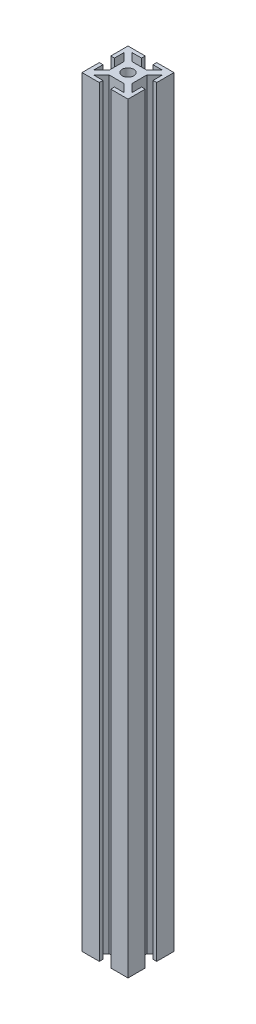
SolidWorks part; units mm, degrees
ref_plane "Front Plane" through (0, 0, 0) normal (0, 0, 1) x (1, 0, 0)
ref_plane "Top Plane" through (0, 0, 0) normal (0, 1, 0) x (1, 0, 0)
ref_plane "Right Plane" through (0, 0, 0) normal (1, 0, 0) x (0, 0, -1)
sketch "Sketch1" plane through (0, 0, 0) normal (0, 1, 0) x (1, 0, 0)
  line L1 (10, -10) -> (-10, -10)
  line L2 (10, -10) -> (10, 10)
  line L3 (10, 10) -> (-10, 10)
  line L4 (-10, -10) -> (-10, 10)
  line L5 (10, -10) -> (-10, 10) construction
  line L6 (10, 10) -> (-10, -10) construction
  line L7 (5, -2.5) -> (10, -2.5)
  line L8 (5, -2.5) -> (5, 2.5)
  line L9 (5, 2.5) -> (10, 2.5)
  line L10 (10, -2.5) -> (10, 2.5)
  line L11 (5, -2.5) -> (10, 2.5) construction
  line L12 (5, 2.5) -> (10, -2.5) construction
  line L13 (2.5, 5) -> (-2.5, 5)
  line L14 (2.5, 5) -> (2.5, 10)
  line L15 (2.5, 10) -> (-2.5, 10)
  line L16 (-2.5, 5) -> (-2.5, 10)
  line L17 (2.5, 5) -> (-2.5, 10) construction
  line L18 (2.5, 10) -> (-2.5, 5) construction
  line L19 (-5, -2.5) -> (-10, -2.5)
  line L20 (-5, -2.5) -> (-5, 2.5)
  line L21 (-5, 2.5) -> (-10, 2.5)
  line L22 (-10, -2.5) -> (-10, 2.5)
  line L23 (-5, -2.5) -> (-10, 2.5) construction
  line L24 (-5, 2.5) -> (-10, -2.5) construction
  line L25 (2.5, -5) -> (-2.5, -5)
  line L26 (2.5, -5) -> (2.5, -10)
  line L27 (2.5, -10) -> (-2.5, -10)
  line L28 (-2.5, -5) -> (-2.5, -10)
  line L29 (2.5, -5) -> (-2.5, -10) construction
  line L30 (2.5, -10) -> (-2.5, -5) construction
  circle A0 centre (0, 0) radius 2.5
  point P0 (0, 0)
  point P6 (7.5, 0)
  point P11 (0, 7.5)
  point P16 (-7.5, 0)
  point P21 (0, -7.5)
  dimension "D5" = 5
  dimension "D1" = 20
  dimension "D2" = 20
  dimension "D3" = 5
  dimension "D4" = 5
extrude "Boss-Extrude1" add sketch "Sketch1" along normal blind 331 contours L28 L25 L26 L1 L2 L7 L8 L9 L3 L14 L13 L16 L4 L21 L20 L19 A0
sketch "Esquisse1" plane through (0, 331, 0) normal (0, 1, 0) x (1, 0, 0)
  line L1 (-10, 2.5) -> (-8.4038, 2.5)
  line L2 (-5, 2.5) -> (-10, 2.5) construction
  line L5 (-2.5, 5) -> (-2.5, 10) construction
  line L8 (-6.5858, 8.4038) -> (-2.5, 8.4038)
  line L9 (-3.182, 5) -> (-6.5858, 8.4038)
  line L10 (-5, 3.182) -> (-8.4038, 6.5858)
  line L11 (-8.4038, 6.5858) -> (-8.4038, 2.5)
  line L12 (-8.4038, 2.5) -> (-5, 2.5)
  line L17 (0, -10.9234) -> (0, 12.7778)
  line L18 (-13.4302, 0) -> (16.5189, 0)
  line L24 (-3.182, -5) -> (-2.5, -5)
  line L25 (-2.5, -5) -> (-2.5, -8.4038)
  line L29 (-2.5, 5) -> (-2.5, 8.4038)
  line L30 (-5, 2.5) -> (-5, 3.182)
  line L31 (-3.182, 5) -> (-2.5, 5)
  line L32 (-8.4038, -2.5) -> (-5, -2.5)
  line L33 (-5, -2.5) -> (-5, -3.182)
  line L34 (-8.4038, -6.5858) -> (-8.4038, -2.5)
  line L35 (-5, -3.182) -> (-8.4038, -6.5858)
  line L36 (-6.5858, -8.4038) -> (-2.5, -8.4038)
  line L37 (-3.182, -5) -> (-6.5858, -8.4038)
  line L38 (6.5858, -8.4038) -> (2.5, -8.4038)
  line L39 (2.5, -5) -> (2.5, -8.4038)
  line L40 (3.182, -5) -> (2.5, -5)
  line L41 (3.182, -5) -> (6.5858, -8.4038)
  line L42 (5, -2.5) -> (5, -3.182)
  line L43 (8.4038, -2.5) -> (5, -2.5)
  line L44 (8.4038, -6.5858) -> (8.4038, -2.5)
  line L45 (5, -3.182) -> (8.4038, -6.5858)
  line L46 (8.4038, 2.5) -> (5, 2.5)
  line L47 (5, 2.5) -> (5, 3.182)
  line L48 (8.4038, 6.5858) -> (8.4038, 2.5)
  line L49 (5, 3.182) -> (8.4038, 6.5858)
  line L50 (3.182, 5) -> (2.5, 5)
  line L51 (2.5, 5) -> (2.5, 8.4038)
  line L52 (3.182, 5) -> (6.5858, 8.4038)
  line L53 (6.5858, 8.4038) -> (2.5, 8.4038)
  circle A1 centre (0, 0) radius 2.5
  point P21 (-4, 4)
extrude "Enlèv. mat.-Extru.1" cut sketch "Esquisse1" against normal up to surface (331 mm away) contours L9 L8 L29 L31 | L12 L30 L10 L11 | L34 L32 L33 L35 | L37 L36 L25 L24 | L41 L38 L39 L40 | L45 L44 L43 L42 | L49 L48 L46 L47 | L52 L53 L51 L50 up to face at (0, 0, 2.5)
